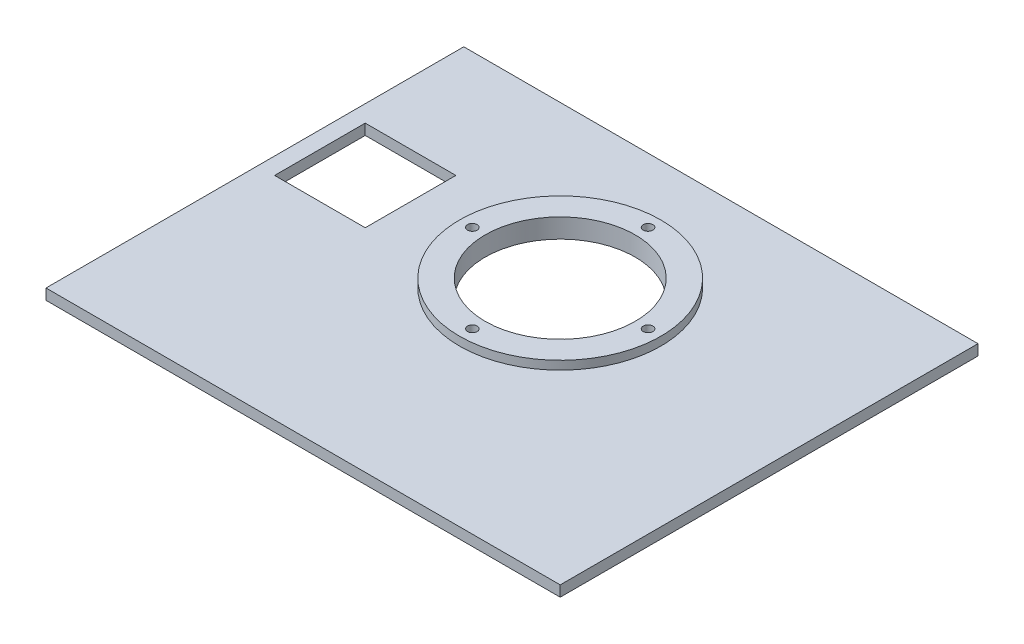
SolidWorks part; units mm, degrees
material "ABS generico"
ref_plane "Piano frontale" through (0, 0, 0) normal (0, 0, 1) x (1, 0, 0)
ref_plane "Piano superiore" through (0, 0, 0) normal (0, 1, 0) x (1, 0, 0)
ref_plane "Piano destro" through (0, 0, 0) normal (1, 0, 0) x (0, 0, -1)
sketch "Schizzo1" plane through (0, 0, 0) normal (0, 1, 0) x (1, 0, 0)
  line L0 (-120, 75) -> (120, 75)
  line L1 (-120, 75) -> (-120, -120)
  line L2 (-120, -120) -> (120, -120)
  line L3 (120, -120) -> (120, 75)
  line L4 (0, -120) -> (0, 75) construction
  circle A1 centre (0, 0) radius 35
  dimension "D1" = 120
  dimension "D2" = 70
  dimension "D3" = 75
  dimension "D4" = 240
extrude "Estrusione-Estrusione1" add sketch "Schizzo1" along normal blind 5
sketch "Schizzo3" plane through (0, 5, 0) normal (0, 1, 0) x (1, 0, 0)
  circle A0 centre (0, 0) radius 47
  circle A1 centre (0, 0) radius 35
  dimension "D1" = 94
extrude "Estrusione-Estrusione2" add sketch "Schizzo3" along normal blind 4
sketch "Schizzo5" plane through (0, 0, 0) normal (0, -1, 0) x (-1, 0, 0)
  line L0 (0, 0) -> (0, 41) construction
  circle A0 centre (0, 0) radius 41 construction
  point P4 (0, 41)
  point P6 (41, 0)
  point P8 (0, -41)
  point P10 (-41, 0)
  dimension "D1" = 82
hole_wizard "Foro per Vite M3-1" positions "Schizzo5" profile "Schizzo6" hole size "M3" standard "ISO"
sketch "Schizzo6" plane through (41, 0, 0) normal (1, 0, 0) x (0, 0, -1)
  line L0 (0, 0) -> (0, 19.4519)
  line L1 (0, 19.4519) -> (2.25, 18.1)
  line L2 (2.25, 18.1) -> (2.25, 0)
  line L5 (2.25, 0) -> (0, 0)
  line L10 (0, 19.4519) -> (-2.25, 18.1) construction
  line L11 (0, -6.35) -> (0, 107.95) construction
  dimension "Hole Dia." = 4.5
  dimension "Hole Depth" = 18.1
  dimension "Drill Angle" = 118
sketch "Schizzo7" plane through (0, 5, 0) normal (0, 1, 0) x (1, 0, 0)
  line L0 (-112.15, 21.15) -> (-69.85, -21.15) construction
  line L1 (-69.85, -21.15) -> (-112.15, -21.15)
  line L2 (-69.85, -21.15) -> (-69.85, 21.15)
  line L3 (-69.85, 21.15) -> (-112.15, 21.15)
  line L4 (-112.15, -21.15) -> (-112.15, 21.15)
  line L5 (-112.15, -21.15) -> (-69.85, 21.15) construction
  line L6 (-91, 0) -> (0, 0) construction
  point P4 (-91, 0)
  dimension "D1" = 91
  dimension "D2" = 42.3
extrude "Taglio-Estrusione1" cut sketch "Schizzo7" against normal blind 14
sketch "Schizzo8" plane through (0, 5, 0) normal (0, 1, 0) x (1, 0, 0)
  line L0 (0, -77.4269) -> (0, -50)
  line L1 (0, 0) -> (-42.3513, 26.5776) construction
  line L2 (0, 0) -> (0, -50) construction
  line L3 (33.9037, -36.7496) -> (78.9041, -58.5434)
  line L4 (42.3513, 26.5776) -> (105.3517, -3.9337)
  line L5 (78.9041, -58.5434) -> (105.3517, -3.9337)
  circle A0 centre (0, 0) radius 50 construction
  arc A1 (-42.3513, 26.5776) -> (0, -50) centre (0, 0) ccw
  circle A2 centre (0, -77.4269) radius 112.2968 construction
  arc A3 (-38.2314, 23.9922) -> (0, -45.1361) centre (0, 0) ccw
  circle A4 centre (0, -77.4269) radius 52.9538 construction
  circle A5 centre (0, 0) radius 50
  circle A6 centre (0, -130.3807) radius 175 construction
  circle A7 centre (0, -130.3807) radius 99 construction
  point P16 (0, 0)
  point P17 (0, 0)
  point P19 (0, -130.3807)
  dimension "D1" = 100
  dimension "D4" = 350
  dimension "D5" = 76
  dimension "D2" = 70
  dimension "D3" = 50
